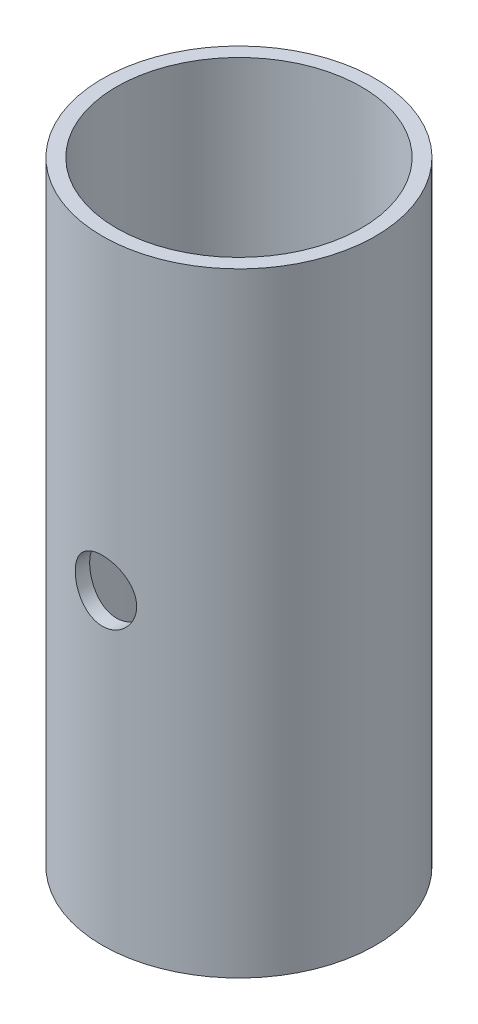
SolidWorks part; units mm, degrees
ref_plane "Front Plane" through (0, 0, 0) normal (0, 0, 1) x (1, 0, 0)
ref_plane "Top Plane" through (0, 0, 0) normal (0, 1, 0) x (1, 0, 0)
ref_plane "Right Plane" through (0, 0, 0) normal (1, 0, 0) x (0, 0, -1)
sketch "Sketch1" plane through (0, 0, 0) normal (0, 1, 0) x (1, 0, 0)
  circle A0 centre (0, 0) radius 9.9695
  circle A1 centre (0, 0) radius 11.1125
  dimension "D1" = 19.939
  dimension "D2" = 22.225
extrude "Boss-Extrude1" add sketch "Sketch1" along normal mid plane 50
sketch "Sketch2" plane through (0, 0, 0) normal (0, 0, 1) x (1, 0, 0)
  circle A0 centre (0, 0) radius 2.5
  dimension "D1" = 5
extrude "Cut-Extrude1" cut sketch "Sketch2" against normal through all both and the other way through all
